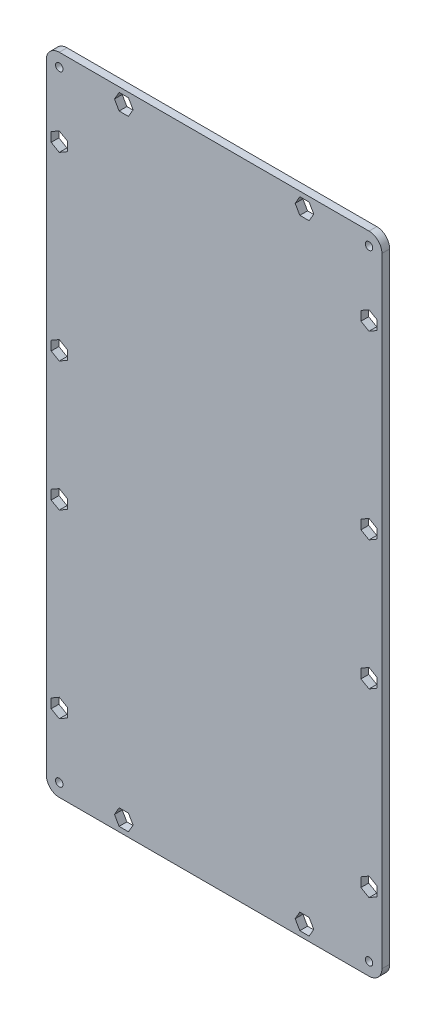
SolidWorks part; units mm, degrees
ref_plane "Front Plane" through (0, 0, 0) normal (0, 0, 1) x (1, 0, 0)
ref_plane "Top Plane" through (0, 0, 0) normal (0, 1, 0) x (1, 0, 0)
ref_plane "Right Plane" through (0, 0, 0) normal (1, 0, 0) x (0, 0, -1)
sketch "Sketch1" plane through (0, 0, 0) normal (0, 0, 1) x (1, 0, 0)
  line L1 (-60, -125) -> (60, -125)
  line L2 (-65, -120) -> (-65, 120)
  line L3 (-60, 125) -> (60, 125)
  line L4 (65, -120) -> (65, 120)
  line L5 (-65, -125) -> (65, 125) construction
  line L6 (-65, 125) -> (65, -125) construction
  arc A0 (60, -125) -> (65, -120) centre (60, -120) ccw
  arc A1 (-60, -125) -> (-65, -120) centre (-60, -120) cw
  arc A2 (-65, 120) -> (-60, 125) centre (-60, 120) cw
  arc A3 (60, 125) -> (65, 120) centre (60, 120) cw
  point P0 (0, 0)
  dimension "D3" = 5
  dimension "D1" = 130
  dimension "D2" = 250
extrude "Boss-Extrude1" add sketch "Sketch1" along normal blind 3
sketch "Sketch2" plane through (0, 0, 3) normal (0, 0, 1) x (1, 0, 0)
  line L0 (-65, 0) -> (65, 0) construction
  line L1 (-65, 120) -> (-65, -120) construction
  line L2 (65, -120) -> (65, 120) construction
  line L3 (0, 125) -> (0, -125) construction
  line L4 (60, 125) -> (-60, 125) construction
  line L5 (-60, -125) -> (60, -125) construction
  line L6 (-60, 120) -> (60, 120) construction
  line L7 (-60, 120) -> (-60, -120) construction
  line L8 (-60, -120) -> (60, -120) construction
  line L9 (60, 120) -> (60, -120) construction
  circle A0 centre (-60, 120) radius 1.45
  circle A4 centre (-60, -120) radius 1.45
  circle A5 centre (60, -120) radius 1.45
  circle A7 centre (60, 120) radius 1.45
  dimension "D1" = 2.9
  dimension "D2" = 5
  dimension "D3" = 5
extrude "Cut-Extrude1" cut sketch "Sketch2" against normal through all
sketch "Sketch3" plane through (0, 0, 3) normal (0, 0, 1) x (1, 0, 0)
  line L0 (0, 120) -> (-60, 120) construction
  line L1 (0, 120) -> (0, 0) construction
  line L2 (0, 0) -> (-65, 0) construction
  line L3 (-65, 120) -> (-65, -120) construction
  line L4 (-60, 120) -> (-60, 0) construction
  line L5 (-33.1958, 123.125) -> (-36.8042, 123.125)
  line L6 (-36.8042, 123.125) -> (-38.6084, 120)
  line L7 (-38.6084, 120) -> (-36.8042, 116.875)
  line L8 (-36.8042, 116.875) -> (-33.1958, 116.875)
  line L9 (-33.1958, 116.875) -> (-31.3916, 120)
  line L10 (-31.3916, 120) -> (-33.1958, 123.125)
  line L12 (-56.875, 96.8042) -> (-60, 98.6084)
  line L13 (-60, 98.6084) -> (-63.125, 96.8042)
  line L14 (-63.125, 96.8042) -> (-63.125, 93.1958)
  line L15 (-63.125, 93.1958) -> (-60, 91.3916)
  line L16 (-60, 91.3916) -> (-56.875, 93.1958)
  line L17 (-56.875, 93.1958) -> (-56.875, 96.8042)
  line L18 (-56.875, 26.8042) -> (-60, 28.6084)
  line L19 (-60, 28.6084) -> (-63.125, 26.8042)
  line L20 (-63.125, 26.8042) -> (-63.125, 23.1958)
  line L21 (-63.125, 23.1958) -> (-60, 21.3916)
  line L22 (-60, 21.3916) -> (-56.875, 23.1958)
  line L23 (-56.875, 23.1958) -> (-56.875, 26.8042)
  circle A0 centre (-35, 120) radius 3.125 construction
  circle A1 centre (-60, 95) radius 3.125 construction
  circle A2 centre (-60, 25) radius 3.125 construction
  dimension "D1" = 6.25
  dimension "D2" = 25
  dimension "D3" = 25
  dimension "D4" = 25
extrude "Cut-Extrude2" cut sketch "Sketch3" against normal through all
mirror "Mirror1" about plane through (0, 0, 0) normal (1, 0, 0) of "Cut-Extrude2"
mirror "Mirror2" about plane through (0, 0, 0) normal (0, 1, 0) of "Cut-Extrude2", "Mirror1"
sketch "Sketch4" plane through (0, 0, 3) normal (0, 0, 1) x (1, 0, 0)
  line L0 (-55, 110) -> (-55, -110) construction
  line L1 (-50, -115) -> (50, -115)
  line L2 (-55, -110) -> (-55, 110)
  line L3 (-50, 115) -> (50, 115)
  line L4 (55, -110) -> (55, 110)
  line L5 (-55, -115) -> (55, 115) construction
  line L6 (-55, 115) -> (55, -115) construction
  line L7 (50, 115) -> (-50, 115) construction
  arc A0 (50, -115) -> (55, -110) centre (50, -110) ccw
  arc A1 (-50, -115) -> (-55, -110) centre (-50, -110) cw
  arc A2 (50, 115) -> (55, 110) centre (50, 110) cw
  arc A3 (-55, 110) -> (-50, 115) centre (-50, 110) cw
  arc A4 (50, -115) -> (55, -110) centre (50, -110) ccw construction
  point P0 (0, 0)
extrude "Cut-Extrude3" [suppressed] cut sketch "Sketch4" against normal through all
surface "Surface-Extrude1" [suppressed] parameters "D1"=7
equation "\"X-ROD-SPACING\"=45"
equation "\"Y-ROD-SPACING\"=75"
equation "\"Z-ROD-SPACING\"=17.5"
equation "\"Y-BED-OFFSET\"=2"
equation "\"Y-BED-ROD-INSET\"=3.5"
equation "\"Y-BED-SCREW-SPACING\"=209"
equation "\"Y-BED-SCREW-CUTOUT-SLOT-HEIGHT\"=2.5"
equation "\"T-SLOT-NUT-FILLET-RADIUS\"=0.5"
equation "\"T-SLOT-SCREW-SHAFT-RADIUS\"=1.55"
equation "\"T-SLOT-SCREW-SHAFT-CUTOUT-LENGTH\"=11"
equation "\"T-SLOT-NUT-DEPTH\"=3.5"
equation "\"T-SLOT-NUT-WIDTH\"=2.85"
equation "\"T-SLOT-NUT-END-DISTANCE\"=8"
equation "\"ACRYLIC-THICKNESS\"=10"
equation "\"ACRYLIC-THICKNESS2\"=4.5"
equation "\"ACRYLIC-TAB-CUTOUT-SIZE\"=\"ACRYLIC-THICKNESS\"+\"ACRYLIC-TAB-TOLERANCE\"*2"
equation "\"ACRYLIC-TAB-TOLERANCE\"=-.05"
equation "\"KERF\"=0.075"
equation "\"ACRYLIC-THICKNESS-TAB-CUTOUT-WIDTH\"=\"ACRYLIC-THICKNESS\"-\"KERF\"*2"
equation "\"ACRYLIC-THICKNESS-TAB-CUTOUT-HEIGHT\"=\"ACRYLIC-TAB-WIDTH\"-\"KERF\"*4"
equation "\"ACRYLIC-THICKNESS2-TAB-CUTOUT-WIDTH\"=\"ACRYLIC-THICKNESS2\"-\"KERF\"*2"
equation "\"ACRYLIC-THICKNESS2-TAB-CUTOUT-HEIGHT\"=\"ACRYLIC-TAB-WIDTH\"-\"KERF\"*4"
equation "\"ACRYLIC-TAB-WIDTH\"=\"ACRYLIC-THICKNESS\""
equation "\"ACRYLIC-M3-HOLE\"=2.9"
equation "\"ACRYLIC-M4-HOLE\"=3.9"
equation "\"SMOOTHROD-CAP-SCREW-DISTANCE\"=20"
equation "\"FRAME-WIDTH-INNER\"=370"
equation "\"NEMA17-HOLE-SPACING\"=31"
equation "\"NEMA17-CENTRAL-CUTOUT\"=22.5"
equation "\"Z-BRACKET-REACH\"=57"
equation "\"Z-ROD-INSET\"=13.5"
equation "\"TOP-BRACKET-SPACING\"=40"
equation "\"SMOOTHROD-X-LENGTH\"=350"
equation "\"SMOOTHROD-Y-LENGTH\"=350"
equation "\"SMOOTHROD-Z-LENGTH\"=350"
equation "\"SMOOTHROD-TIGHTENING-HEADROOM\"=.25"
equation "\"LEADSCREW-Z-LENGTH\"=300"
equation "\"SCREW-LENGTH-FRAME\"=\"ACRYLIC-THICKNESS\" + 10"
equation "\"SCREW-LENGTH-MOTOR\"=\"ACRYLIC-THICKNESS\" + 5"
equation "\"SCREW-LENGTH-EXTRUDER\"=28"
equation "\"SCREW-HEAD-RADIUS\"=6"
equation "\"PRINTED-M3-HOLE\"=3.5"
equation "\"PRINTED-X-SMOOTHROD-DIAMETER\"=8.8"
equation "\"PRINTED-X-SMOOTHROD-CUTOUT\"=10"
equation "\"PRINTED-X-BASE-HEIGHT\"=10"
equation "\"PRINTED-LM8UU-CUTOUT-SIZE\"=15.5"
equation "\"PRINTED-LM8UU-CUTOUT-LENGTH\"=24.5"
equation "\"PRINTED-X-IDLER-HEIGHT\"=16"
equation "\"PRINTED-M3-NUT-AF\"=6.25"
equation "\"PSU-MOUNTING-WIDTH\"=50"
equation "\"PSU-MOUNTING-HEIGHT\"=150"
equation "\"Y-BELT-TO-ROD-DISTANCE\"=20"
equation "\"SPOOL-HOLDER-ROD-SPACING\"=150"
equation "\"ACRYLIC-X-CARRIAGE-WIDTH\"=55"
equation "\"ACRYLIC-X-CARRIAGE-HEIGHT\"=75"
equation "\"ACRYLIC-X-CARRIAGE-LM8UU-CUTOUT-WIDTH\"=24.25"
equation "\"ACRYLIC-X-CARRIAGE-LM8UU-CUTOUT-HEIGHT\"=11.0"
equation "\"ACRYLIC-X-CARRIAGE-SCREW-SPACING-X\"=15"
equation "\"ACRYLIC-X-CARRIAGE-SCREW-SPACING-Y\"=33"
equation "\"ACRYLIC-X-CARRIAGE-CENTER-TAB-SPACING\"=14"
equation "\"ACRYLIC-X-CARRIAGE-EXTRUDER-OFFSET\"=26"
equation "\"ACRYLIC-X-CARRIAGE-EXTRUDER-ANGLE\"=90"
equation "\"ACRYLIC-X-CARRIAGE-EXTRUDER-SHELF-DEPTH\"=\"ACRYLIC-X-CARRIAGE-EXTRUDER-OFFSET\" + 28"
equation "\"ACRYLIC-X-CARRIAGE-EXTRUDER-BRACE-SPACING\"=23"
equation "\"ACRYLIC-X-CARRIAGE-EXTRUDER-BRACE-TAB-OFFSET\"=20"
equation "\"ACRYLIC-X-CARRIAGE-EXTRUDER-BRACE-HEIGHT\"=35"
equation "\"ACRYLIC-X-CARRIAGE-EXTRUDER-BRACE-SCREW-SPACING\"=22"
equation "\"ACRYLIC-X-CARRIAGE-DUAL-WIDTH-MULTIPLIER\"=1.65"
equation "\"ACRYLIC-X-CARRIAGE-DUAL-HOTEND-SPACING\"=42"
equation "\"ACRYLIC-X-CARRIAGE-DUAL-WIDTH\"=75"
equation "\"ACRYLIC-X-CARRIAGE-DUAL-FAN-OFFSET\"=52"
equation "\"ACRYLIC-X-CARRIAGE-DUAL-FAN-HEIGHT\"=20"
equation "\"ACRYLIC-X-CARRIAGE-DUAL-HOTEND-SEPARATION\"=36"
equation "\"ACRYLIC-X-CARRIAGE-DUAL-MOUNT-PLATE-DEPTH\"=75"
equation "\"ACRYLIC-X-CARRIAGE-DUAL-MOUNT-BRACE-WIDTH\"=33"
equation "\"ACRYLIC-X-CARRIAGE-DUAL-MOUNT-SCREW-WIDTH\"=40"
equation "\"BLOWER-FAN-WIDTH\"=15"
equation "\"D1@Sketch3\"=\"PRINTED-M3-NUT-AF\""
